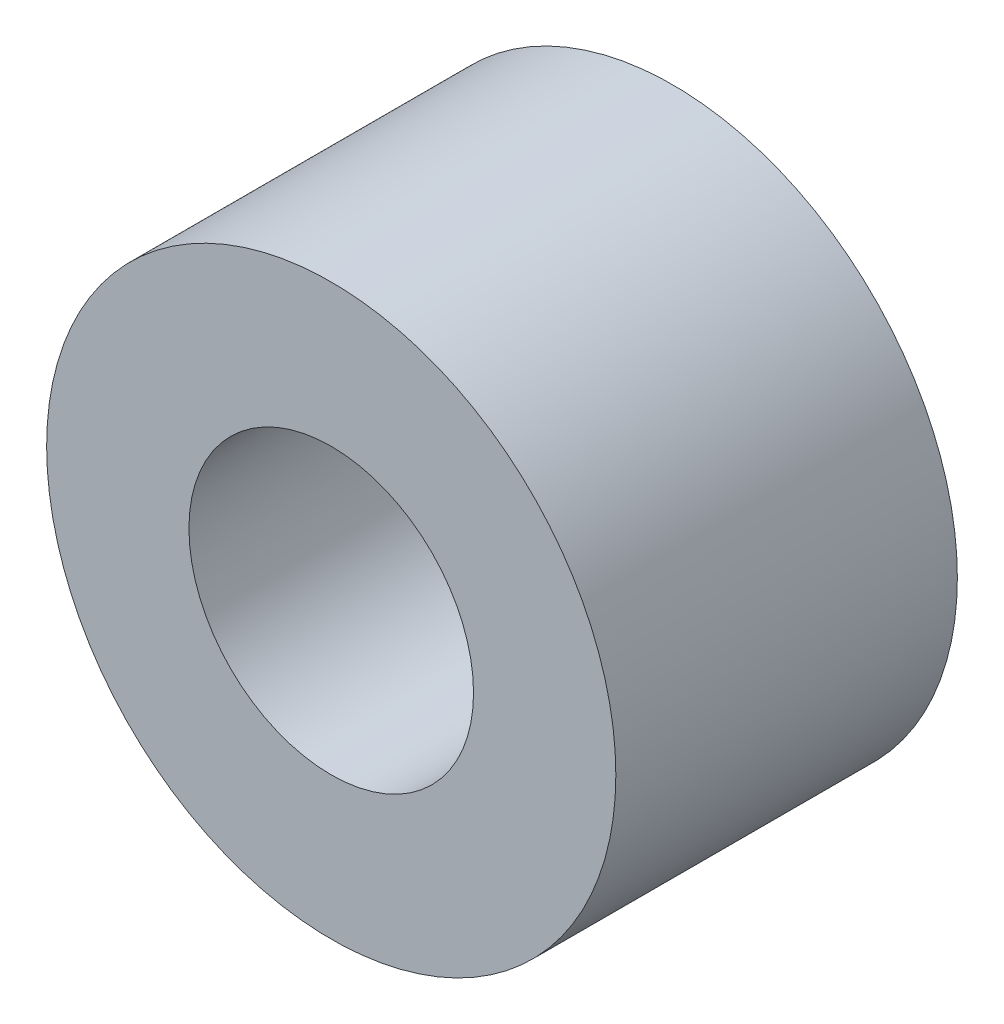
SolidWorks part; units mm, degrees
ref_plane "前视基准面" through (0, 0, 0) normal (0, 0, 1) x (1, 0, 0)
ref_plane "上视基准面" through (0, 0, 0) normal (0, 1, 0) x (1, 0, 0)
ref_plane "右视基准面" through (0, 0, 0) normal (1, 0, 0) x (0, 0, -1)
sketch "草图1" plane through (0, 0, 0) normal (0, 0, 1) x (1, 0, 0)
  circle A0 centre (-19.85, -19.85) radius 2.5
  circle A1 centre (-19.85, -19.85) radius 5
  dimension "D1" = 5
  dimension "D2" = 10
extrude "凸台-拉伸1" add sketch "草图1" along normal blind 6
